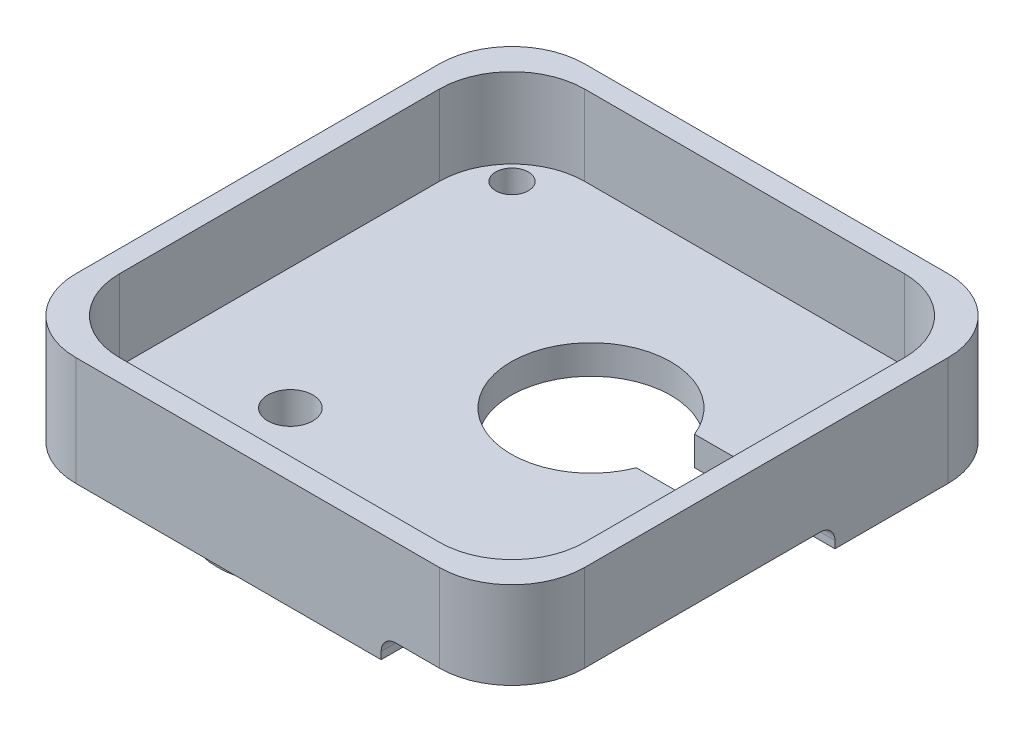
SolidWorks part; units mm, degrees
ref_plane "Front Plane" through (0, 0, 0) normal (0, 0, 1) x (1, 0, 0)
ref_plane "Top Plane" through (0, 0, 0) normal (0, 1, 0) x (1, 0, 0)
ref_plane "Right Plane" through (0, 0, 0) normal (1, 0, 0) x (0, 0, -1)
sketch "Sketch1" plane through (0, 0, 0) normal (0, 1, 0) x (1, 0, 0)
  line L0 (-50.25, 10) -> (-50.25, 0) construction
  line L1 (-10, 0) -> (-60, 0)
  line L2 (0, 10) -> (0, 60)
  line L3 (-10, 70) -> (-60, 70)
  line L4 (-70, 10) -> (-70, 60)
  line L5 (-60, 19.75) -> (-70, 19.75) construction
  line L6 (-50.25, 19.75) -> (-29.5671, 40.4329)
  line L7 (-29.5671, 59.9329) -> (-29.5671, 70) construction
  line L8 (-10.0671, 40.4329) -> (0, 40.4329) construction
  circle A0 centre (-29.5671, 40.4329) radius 19.5
  circle A1 centre (-50.25, 19.75) radius 9.75
  arc A2 (-60, 0) -> (-70, 10) centre (-60, 10) cw
  arc A3 (-10, 0) -> (0, 10) centre (-10, 10) ccw
  arc A4 (0, 60) -> (-10, 70) centre (-10, 60) ccw
  arc A5 (-60, 70) -> (-70, 60) centre (-60, 60) ccw
  circle A6 centre (-50.25, 19.75) radius 2.5
  circle A7 centre (-29.5671, 40.4329) radius 2.5
  point P16 (-70, 0)
  point P19 (0, 0)
  point P24 (-70, 70)
  dimension "D3" = 39
  dimension "D4" = 19.5
  dimension "D8" = 10
  dimension "D9" = 5
  dimension "D10" = 5
  dimension "D11" = 10.0671
  dimension "D1" = 70
  dimension "D2" = 70
  dimension "D5" = 10
  dimension "D6" = 10
  dimension "D7" = 45
  dimension "D12" = 10.0671
extrude "Boss-Extrude2" add sketch "Sketch1" along normal blind 4 contours L3 A5 L4 A2 L1 A3 L2 A4 A0 A1 | A0 A7 | A1 A6
sketch "Sketch2" plane through (0, 4, 0) normal (0, 1, 0) x (1, 0, 0)
  line L0 (-3, 13) -> (-3, 57)
  line L1 (-10, 0) -> (-60, 0)
  line L2 (0, 10) -> (0, 60)
  line L3 (-10, 70) -> (-60, 70)
  line L4 (-70, 10) -> (-70, 60)
  line L5 (-13, 67) -> (-57, 67)
  line L6 (-67, 13) -> (-67, 57)
  line L7 (-13, 3) -> (-57, 3)
  line L8 (0, 0) -> (-70, 0) construction
  line L9 (-70, 0) -> (-70, 70) construction
  line L10 (-3, 3) -> (-67, 3) construction
  line L11 (-67, 3) -> (-67, 67) construction
  line L12 (-3, 3) -> (-3, 67) construction
  line L13 (0, 0) -> (0, 70) construction
  line L14 (-3, 67) -> (-67, 67) construction
  line L15 (0, 70) -> (-70, 70) construction
  line L16 (-70, 10) -> (-70, 60) construction
  line L17 (0, 10) -> (0, 60) construction
  line L18 (-10, 70) -> (-60, 70) construction
  arc A0 (-60, 0) -> (-70, 10) centre (-60, 10) cw
  arc A1 (-57, 3) -> (-67, 13) centre (-57, 13) cw
  arc A2 (-13, 3) -> (-3, 13) centre (-13, 13) ccw
  arc A3 (-10, 0) -> (0, 10) centre (-10, 10) ccw
  arc A4 (-3, 57) -> (-13, 67) centre (-13, 57) ccw
  arc A5 (0, 60) -> (-10, 70) centre (-10, 60) ccw
  arc A6 (-67, 57) -> (-57, 67) centre (-57, 57) cw
  arc A7 (-70, 60) -> (-60, 70) centre (-60, 60) cw
  dimension "D2" = 10
  dimension "D1" = 3
extrude "Boss-Extrude3" add sketch "Sketch2" along normal blind 11
sketch "Sketch3" plane through (0, 0, 0) normal (0, -1, 0) x (1, 0, 0)
  circle A0 centre (-50.25, -19.75) radius 3.1
  dimension "D1" = 6.2
extrude "Cut-Extrude1" cut sketch "Sketch3" against normal blind 8.5
sketch "Sketch4" plane through (0, 0, 0) normal (0, -1, 0) x (1, 0, 0)
  circle A0 centre (-50.25, -19.75) radius 10
  circle A1 centre (-50.25, -19.75) radius 3.1
  dimension "D1" = 20
extrude "Boss-Extrude4" add sketch "Sketch4" along normal blind 10
sketch "Sketch5" plane through (0, -10, 0) normal (0, -1, 0) x (1, 0, 0)
  line L0 (-50.25, -19.75) -> (-50.25, -9.75) construction
  line L2 (-53.15, -11.85) -> (-47.35, -11.85)
  line L3 (-53.15, -11.85) -> (-53.15, -14.65)
  line L4 (-53.15, -14.65) -> (-47.35, -14.65)
  line L5 (-47.35, -11.85) -> (-47.35, -14.65)
  circle A0 centre (-50.25, -19.75) radius 10 construction
  dimension "D1" = 2.1
  dimension "D2" = 2.8
  dimension "D3" = 5.8
  dimension "D4" = 2.9
extrude "Cut-Extrude2" cut sketch "Sketch5" against normal blind 8.8
sketch "Sketch6" plane through (0, -10, 0) normal (0, -1, 0) x (1, 0, 0)
  line L0 (-50.25, -19.75) -> (-50.25, -9.75) construction
  circle A0 centre (-50.25, -19.75) radius 10 construction
ref_plane "Plane1" through (-50.25, -10, -9.75) normal (0, 0, 1) x (1, 0, 0)
sketch "Sketch7" plane through (-50.25, -10, -9.75) normal (0, 0, 1) x (1, 0, 0)
  line L0 (0, 0) -> (0, 10) construction
  line L1 (-10, 0) -> (10, 0) construction
  line L2 (-10, 10) -> (10, 10) construction
  circle A0 centre (0, 5) radius 1.6
  dimension "D1" = 3.2
extrude "Cut-Extrude3" cut sketch "Sketch7" against normal blind 10
ref_plane "Plane2" through (0, 0, -37.5) normal (0, 0, 1) x (1, 0, 0)
ref_plane "Plane3" through (-37.5, 0, 0) normal (1, 0, 0) x (0, 0, -1)
sketch "Sketch13" plane through (0, 0, 0) normal (0, -1, 0) x (1, 0, 0)
  circle A0 centre (-29.5671, -40.4329) radius 11
  dimension "D1" = 22
extrude "Cut-Extrude6" cut sketch "Sketch13" against normal blind 10
sketch "Sketch14" plane through (0, 4, 0) normal (0, 1, 0) x (1, 0, 0)
  line L0 (0, 10) -> (0, 60) construction
  line L1 (-10, 70) -> (-60, 70) construction
  line L2 (-35, 70) -> (-35, 0) construction
  line L3 (-60, 0) -> (-10, 0) construction
  line L4 (0, 35) -> (-70, 35) construction
  line L5 (-70, 60) -> (-70, 10) construction
  circle A0 centre (-8, 62) radius 2.25
  circle A1 centre (-62, 62) radius 2.25
  circle A2 centre (-62, 8) radius 2.25
  circle A3 centre (-8, 8) radius 2.25
  dimension "D1" = 4.5
  dimension "D2" = 8
  dimension "D3" = 8
extrude "Cut-Extrude7" cut sketch "Sketch14" against normal blind 10
sketch "Sketch15" plane through (0, 0, 0) normal (0, -1, 0) x (1, 0, 0)
  line L0 (-29.5671, -40.4329) -> (-11.5671, -40.4329) construction
  line L1 (-12.0172, -36.4329) -> (-19.3202, -36.4329)
  line L2 (-12.0172, -44.4329) -> (-19.3202, -44.4329)
  circle A0 centre (-29.5671, -40.4329) radius 18
  circle A1 centre (-29.5671, -40.4329) radius 11 construction
  circle M8 centre (-29.5671, -40.4329) radius 11
  dimension "D1" = 36
  dimension "D2" = 4
extrude "Cut-Extrude8" cut sketch "Sketch15" against normal blind 10 contours L0 A0 L1 M8 | L0 L2 A0 M8
sketch "Sketch16" plane through (0, 0, 0) normal (0, -1, 0) x (1, 0, 0)
  line L0 (-29.5671, -40.4329) -> (-11.5671, -40.4329) construction
  line L1 (0, 0) -> (-18, 0)
  line L2 (0, 0) -> (0, -44.4329)
  line L3 (0, -44.4329) -> (-18, -44.4329)
  line L4 (-18, 0) -> (-18, -44.4329)
  arc A0 (-12.0172, -44.4329) -> (-12.0172, -36.4329) centre (-29.5671, -40.4329) ccw construction
  dimension "D1" = 4
  dimension "D2" = 18
extrude "Cut-Extrude9" cut sketch "Sketch16" against normal blind 3
fillet "Fillet1" radius 2 2 edges at (-18, 3, -18.2164) (-6.0086, 3, -44.4329)
